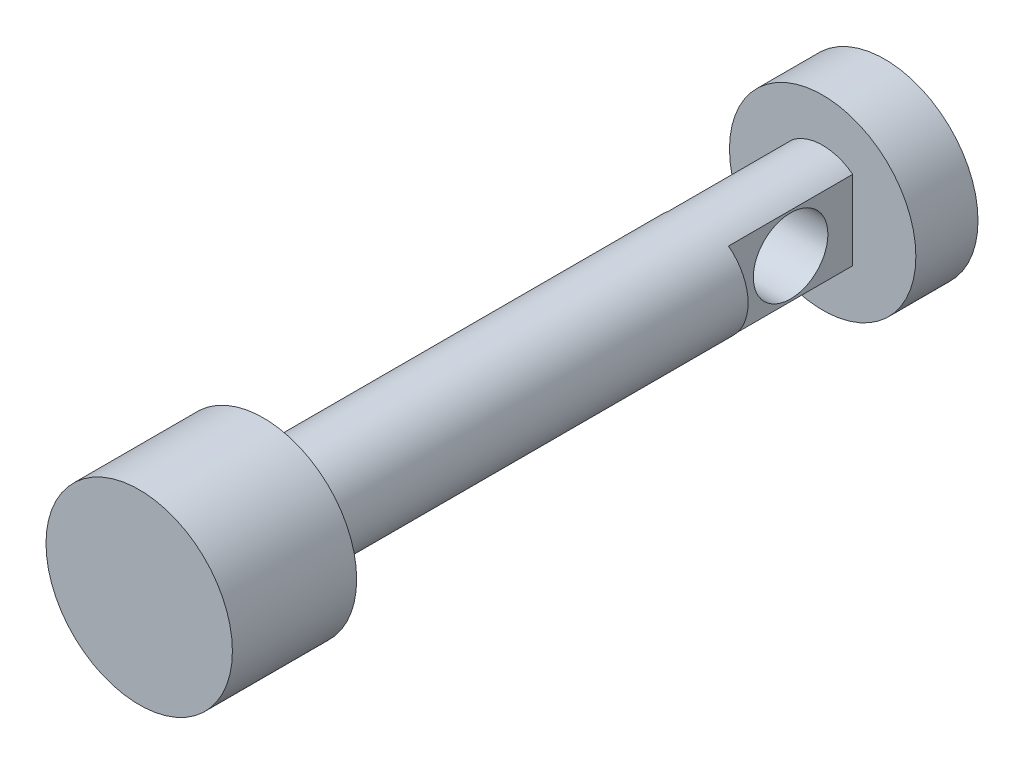
SolidWorks part; units mm, degrees
material "AISI 347 Aço inoxidável recozido (SS)"
ref_plane "Plano frontal" through (0, 0, 0) normal (0, 0, 1) x (1, 0, 0)
ref_plane "Plano superior" through (0, 0, 0) normal (0, 1, 0) x (1, 0, 0)
ref_plane "Plano direito" through (0, 0, 0) normal (1, 0, 0) x (0, 0, -1)
sketch "Esboço1" plane through (0, 0, 0) normal (1, 0, 0) x (0, 0, -1)
  line L0 (-60, 0) -> (60, 0)
  line L1 (-60, 0) -> (-60, 15)
  line L2 (-60, 15) -> (-40, 15)
  line L3 (-40, 15) -> (-40, 8)
  line L4 (-40, 8) -> (60, 8)
  line L5 (60, 8) -> (60, 0)
  dimension "D1" = 120
  dimension "D2" = 20
  dimension "D3" = 15
  dimension "D4" = 8
revolve "Revolução1" add sketch "Esboço1" angle 360 about L0
sketch "Esboço2" plane through (0, 0, 0) normal (1, 0, 0) x (0, 0, -1)
  circle A0 centre (40, 0) radius 6
  dimension "D1" = 12
  dimension "D2" = 40
extrude "Corte-extrusão1" cut sketch "Esboço2" against normal through all both and the other way through all
sketch "Esboço3" plane through (0, 0, -60) normal (0, 0, -1) x (-1, 0, 0)
  line L1 (-4.8391, 6.3705) -> (4.8391, 6.3705)
  line L2 (-4.8391, 6.3705) -> (-4.8391, -6.3705)
  line L3 (-4.8391, -6.3705) -> (4.8391, -6.3705)
  line L4 (4.8391, 6.3705) -> (4.8391, -6.3705)
  circle A0 centre (0, 0) radius 8 construction
  circle A1 centre (0, 0) radius 8
  circle A2 centre (0, 0) radius 8
  circle A3 centre (0, 0) radius 8 construction
  circle M6 centre (0, 0) radius 8
  dimension "D1" = 0
extrude "Corte-extrusão2" cut sketch "Esboço3" against normal blind 30 contours L2 M6 | L4 M6
sketch "Sketch1" plane through (0, 0, -60) normal (0, 0, -1) x (-1, 0, 0)
  circle A0 centre (0, 0) radius 15
extrude "Boss-Extrude1" add sketch "Sketch1" against normal blind 10
